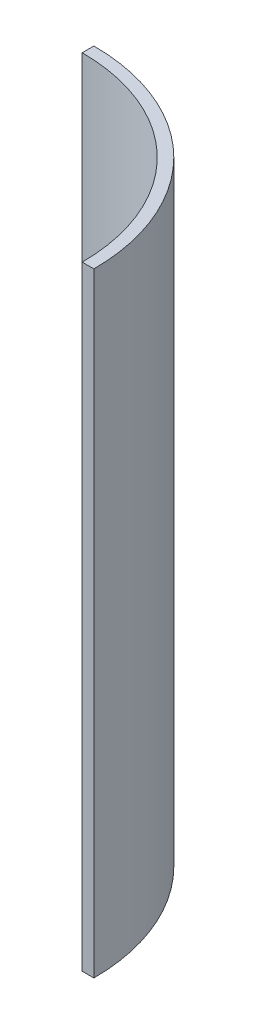
SolidWorks part; units mm, degrees
ref_plane "Front Plane" through (0, 0, 0) normal (0, 0, 1) x (1, 0, 0)
ref_plane "Top Plane" through (0, 0, 0) normal (0, 1, 0) x (1, 0, 0)
ref_plane "Right Plane" through (0, 0, 0) normal (1, 0, 0) x (0, 0, -1)
sketch "Sketch2" plane through (0, 5, 0) normal (0, 1, 0) x (1, 0, 0)
  circle A0 centre (0, 0) radius 33
  circle A2 centre (0, 0) radius 31
  dimension "D2" = 66
  dimension "D3" = 62
extrude "Boss-Extrude2" add sketch "Sketch2" along normal blind 105 separate body
sketch "Sketch3" plane through (0, 115, 0) normal (0, 1, 0) x (1, 0, 0)
  line L0 (35, 0) -> (0, 0)
  line L1 (0, 0) -> (0, 35)
  circle A0 centre (0, 0) radius 35 construction
  arc A1 (35, 0) -> (0, 35) centre (0, 0) cw
extrude "Cut-Extrude1" cut sketch "Sketch3" against normal blind 110
